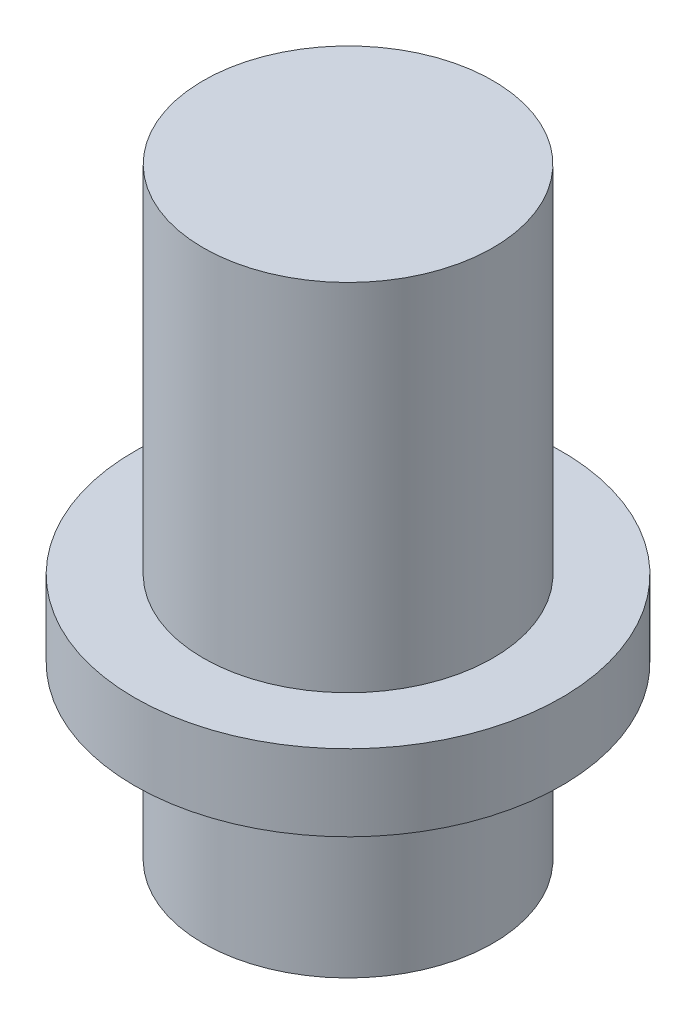
SolidWorks part; units mm, degrees
ref_plane "Front Plane" through (0, 0, 0) normal (0, 0, 1) x (1, 0, 0)
ref_plane "Top Plane" through (0, 0, 0) normal (0, 1, 0) x (1, 0, 0)
ref_plane "Right Plane" through (0, 0, 0) normal (1, 0, 0) x (0, 0, -1)
sketch "Sketch1" plane through (0, 0, 0) normal (0, 1, 0) x (1, 0, 0)
  circle A0 centre (0, 0) radius 9.5
  dimension "D1" = 19
extrude "Boss-Extrude1" add sketch "Sketch1" along normal blind 11.2
sketch "Sketch2" plane through (0, 11.2, 0) normal (0, 1, 0) x (1, 0, 0)
  circle A0 centre (0, 0) radius 14
  dimension "D1" = 28
extrude "Boss-Extrude2" add sketch "Sketch2" along normal blind 5
sketch "Sketch3" plane through (0, 16.2, 0) normal (0, 1, 0) x (1, 0, 0)
  circle A0 centre (0, 0) radius 9.5
  dimension "D1" = 19
extrude "Boss-Extrude3" add sketch "Sketch3" along normal blind 23.3
